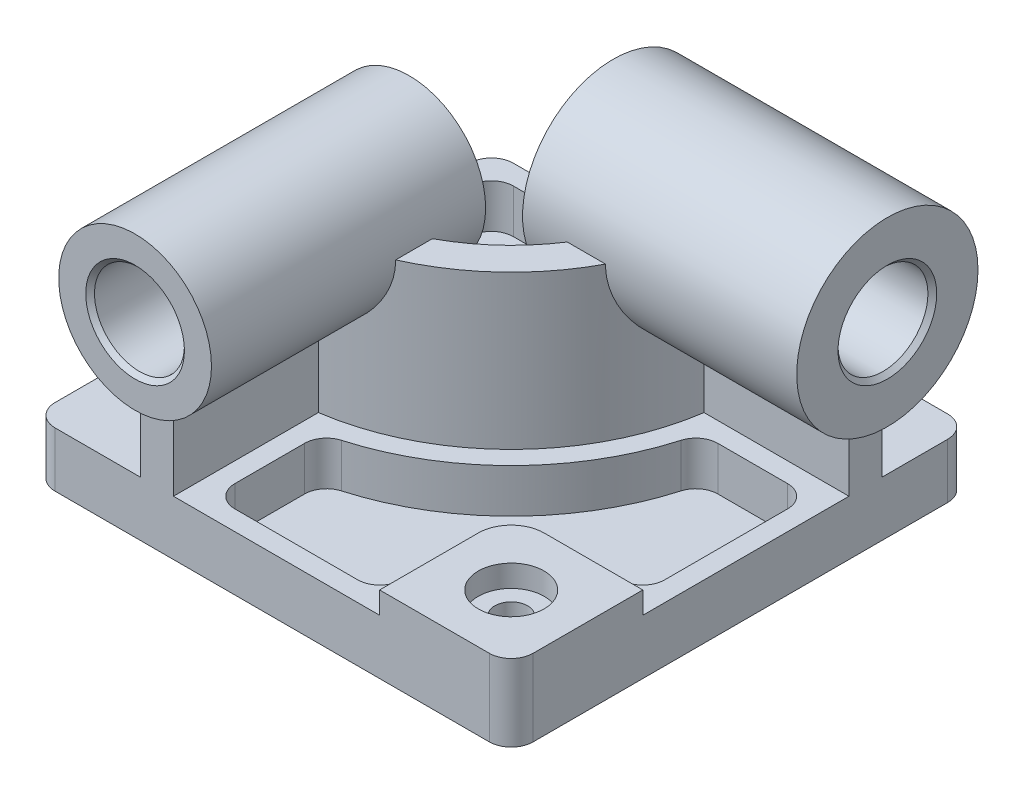
SolidWorks part; units mm, degrees
material "Alloy Steel"
ref_plane "Front Plane" through (0, 0, 0) normal (0, 0, 1) x (1, 0, 0)
ref_plane "Top Plane" through (0, 0, 0) normal (0, 1, 0) x (1, 0, 0)
ref_plane "Right Plane" through (0, 0, 0) normal (1, 0, 0) x (0, 0, -1)
sketch "Sketch1" plane through (0, 0, 0) normal (0, 1, 0) x (1, 0, 0)
  line L0 (0, 0) -> (0, -169) construction
  line L1 (-39, 40) -> (159, 40)
  line L2 (-49, 30) -> (-49, -159)
  line L3 (-39, -169) -> (159, -169)
  line L4 (169, 30) -> (169, -159)
  line L6 (21.1729, -100.3509) -> (22.0551, -100.3509) construction
  line L8 (0, 0) -> (169, 0) construction
  arc A0 (-39, 40) -> (-49, 30) centre (-39, 30) ccw
  arc A1 (-49, -159) -> (-39, -169) centre (-39, -159) ccw
  arc A2 (159, -169) -> (169, -159) centre (159, -159) ccw
  arc A3 (159, 40) -> (169, 30) centre (159, 30) cw
  dimension "D5" = 10
  dimension "D1" = 169
  dimension "D2" = 169
  dimension "D3" = 209
  dimension "D4" = 218
extrude "Boss-Extrude1" add sketch "Sketch1" along normal blind 25
sketch "Sketch2" plane through (0, 25, 0) normal (0, 1, 0) x (1, 0, 0)
  line L0 (0, -89) -> (0, -169)
  line L1 (-39, -169) -> (159, -169) construction
  line L2 (89, 0) -> (169, 0)
  line L3 (169, -159) -> (169, 30) construction
  line L4 (15, -102.9126) -> (15, -169)
  line L5 (102.9126, -15) -> (169, -15)
  line L6 (169, 0) -> (169, -15)
  line L7 (0, -169) -> (15, -169)
  arc A0 (0, -89) -> (89, 0) centre (0, 0) ccw
  arc A1 (15, -102.9126) -> (102.9126, -15) centre (0, 0) ccw
  dimension "D1" = 80
  dimension "D2" = 15
extrude "Boss-Extrude2" add sketch "Sketch2" along normal blind 95 from surface at -25 starting at face at (60, 0, 64.5)
sketch "Sketch3" plane through (0, 25, 0) normal (0, 1, 0) x (1, 0, 0)
  line L0 (15, -169) -> (159, -169) construction
  line L1 (124, -109) -> (169, -109)
  line L2 (109, -124) -> (109, -169)
  line L3 (109, -169) -> (159, -169)
  line L4 (169, -109) -> (169, -159)
  line L5 (169, -159) -> (169, -15) construction
  arc A0 (159, -169) -> (169, -159) centre (159, -159) ccw construction
  arc A1 (159, -169) -> (169, -159) centre (159, -159) ccw
  arc A2 (124, -109) -> (109, -124) centre (124, -124) ccw
  dimension "D3" = 15
  dimension "D1" = 60
  dimension "D2" = 60
extrude "Boss-Extrude3" add sketch "Sketch3" along normal blind 10
hole_wizard "CBORE for M8 Hex Head Bolt1" positions "Sketch5" profile "Sketch4" counterbore size "M8" standard "ANSI Metric" end condition through all
sketch "Sketch5" plane through (0, 35, 0) normal (0, 1, 0) x (1, 0, 0)
  line L0 (109, -169) -> (159, -169) construction
  line L2 (169, -159) -> (169, -109) construction
  point P0 (139, -139)
  dimension "D1" = 30
  dimension "D2" = 30
sketch "Sketch4" plane through (139, 35, 139) normal (1, 0, 0) x (0, 0, 1)
  line L0 (0, 0) -> (0, 35)
  line L1 (0, 35) -> (7.5, 35)
  line L3 (7.5, 35) -> (7.5, 10)
  line L4 (7.5, 10) -> (15, 10)
  line L5 (15, 10) -> (15, 0)
  line L7 (15, 0) -> (0, 0)
  line L11 (0, -6.35) -> (0, 107.95) construction
  dimension "Thru Hole Dia." = 15
  dimension "Thru Hole Depth" = 35
  dimension "C'Bore Dia." = 30
  dimension "C'Bore Depth" = 10
sketch "Sketch6" plane through (0, 25, 0) normal (0, 1, 0) x (1, 0, 0)
  line L6 (100, -160) -> (100, -124)
  line L7 (100, -150) -> (100, -124)
  line L8 (124, -100) -> (160, -100)
  line L9 (124, -100) -> (150, -100)
  line L10 (160, -24) -> (110.4219, -24)
  line L11 (150, -24) -> (118.2074, -24)
  line L12 (24, -160) -> (100, -160)
  line L13 (24, -110.4219) -> (24, -160)
  line L14 (24, -118.2074) -> (24, -150)
  line L15 (160, -100) -> (160, -24)
  line L18 (34, -160) -> (90, -160)
  line L21 (160, -90) -> (160, -34)
  arc A0 (160, -90) -> (150, -100) centre (150, -90) cw
  arc A1 (100, -150) -> (90, -160) centre (90, -150) cw
  arc A2 (24, -118.2074) -> (31.2358, -108.5971) centre (34, -118.2074) cw
  arc A3 (108.5971, -31.2358) -> (118.2074, -24) centre (118.2074, -34) cw
  arc A4 (124, -100) -> (100, -124) centre (124, -124) ccw
  arc A5 (24, -110.4219) -> (110.4219, -24) centre (0, 0) ccw
  arc A6 (124, -100) -> (100, -124) centre (124, -124) ccw
  arc A7 (31.2358, -108.5971) -> (108.5971, -31.2358) centre (0, 0) ccw
  arc A8 (160, -34) -> (150, -24) centre (150, -34) ccw
  arc A9 (34, -160) -> (24, -150) centre (34, -150) cw
  dimension "D2" = 10
  dimension "D3" = 10
  dimension "D1" = 9
extrude "Cut-Extrude1" cut sketch "Sketch6" against normal offset from surface (20 mm away) 5 up to face at (139, 0, 146.5)
sketch "Sketch7" plane through (0, 0, 169) normal (0, 0, 1) x (1, 0, 0)
  line L0 (0, 95) -> (15, 95) construction
  circle A0 centre (7.5, 95) radius 34.8333
  dimension "D1" = 69.6667
extrude "Boss-Extrude4" add sketch "Sketch7" against normal blind 125 from offset 10
sketch "Sketch8" plane through (169, 0, 0) normal (1, 0, 0) x (0, 0, -1)
  line L0 (-15, 95) -> (0, 95) construction
  circle A0 centre (-7.5, 95) radius 41.3333
  dimension "D1" = 82.6667
extrude "Boss-Extrude5" add sketch "Sketch8" against normal blind 125 from offset 10
sketch "Sketch9" plane through (0, 0, 179) normal (0, 0, 1) x (1, 0, 0)
  circle A0 centre (7.5, 95) radius 20.5
  dimension "D1" = 41
extrude "Cut-Extrude2" cut sketch "Sketch9" against normal up to next
sketch "Sketch10" plane through (179, 0, 0) normal (1, 0, 0) x (0, 0, -1)
  circle A0 centre (-7.5, 95) radius 20.5
  dimension "D1" = 41
extrude "Cut-Extrude3" cut sketch "Sketch10" against normal up to next
chamfer "Chamfer1" distance 2 angle 45 4 edges at (54, 95, -13) (28, 95, 54) (179, 95, -13) (28, 95, 179)
sketch "Sketch11" plane through (0, 25, 0) normal (0, 1, 0) x (1, 0, 0)
  line L6 (0, -80) -> (-40, -80)
  line L7 (80, 0) -> (80, 31)
  line L8 (-40, 30) -> (-40, 31)
  line L9 (-40, 31) -> (-39, 31)
  line L12 (79.4921, 9) -> (160, 9)
  line L13 (160, 9) -> (160, 30)
  line L14 (159, 31) -> (-39, 31)
  line L15 (-40, 30) -> (-40, -159)
  line L16 (-39, -160) -> (-9, -160)
  line L17 (-9, -160) -> (-9, -79.4921)
  line L20 (80, 31) -> (-39, 31)
  line L21 (-40, 30) -> (-40, -80)
  arc A8 (-9, -79.4921) -> (79.4921, 9) centre (0, 0) ccw
  arc A9 (160, 30) -> (159, 31) centre (159, 30) ccw
  arc A10 (-39, 31) -> (-40, 30) centre (-39, 30) ccw
  arc A11 (-40, -159) -> (-39, -160) centre (-39, -159) ccw
  arc A12 (0, -80) -> (80, 0) centre (0, 0) ccw
  arc A14 (-39, 31) -> (-40, 30) centre (-39, 30) ccw construction
  dimension "D1" = 9
extrude "Cut-Extrude4" cut sketch "Sketch11" against normal up to surface (20 mm away) up to face at (98.5987, 5, 98.5987)
fillet "Fillet1" radius 10 3 edges at (-40, 15, -31) (-40, 15, 80) (80, 15, -31)
equation "\"A\"= 209"
equation "\"D1@Sketch1\"=\"C\""
equation "\"D2@Sketch1\"=\"C\""
equation "\"B\"= 218"
equation "\"D3@Sketch1\"=\"A\""
equation "\"C\"= 169"
equation "\"D4@Sketch1\"=\"B\""
equation "\"D1@Sketch7\"=\"X\""
equation "\"D\"= 125"
equation "\"D1@Boss-Extrude4\"=\"D\""
equation "\"D1@Sketch8\"=\"Y\""
equation "\"D1@Boss-Extrude5\"=\"D\""
equation "\"E\"= 41"
equation "\"D1@Sketch9\"=\"E\""
equation "\"D1@Sketch10\"=\"E\""
equation "\"X\"= \"A\" / 3"
equation "\"Y\"= \"B\" / 3 + 10"
